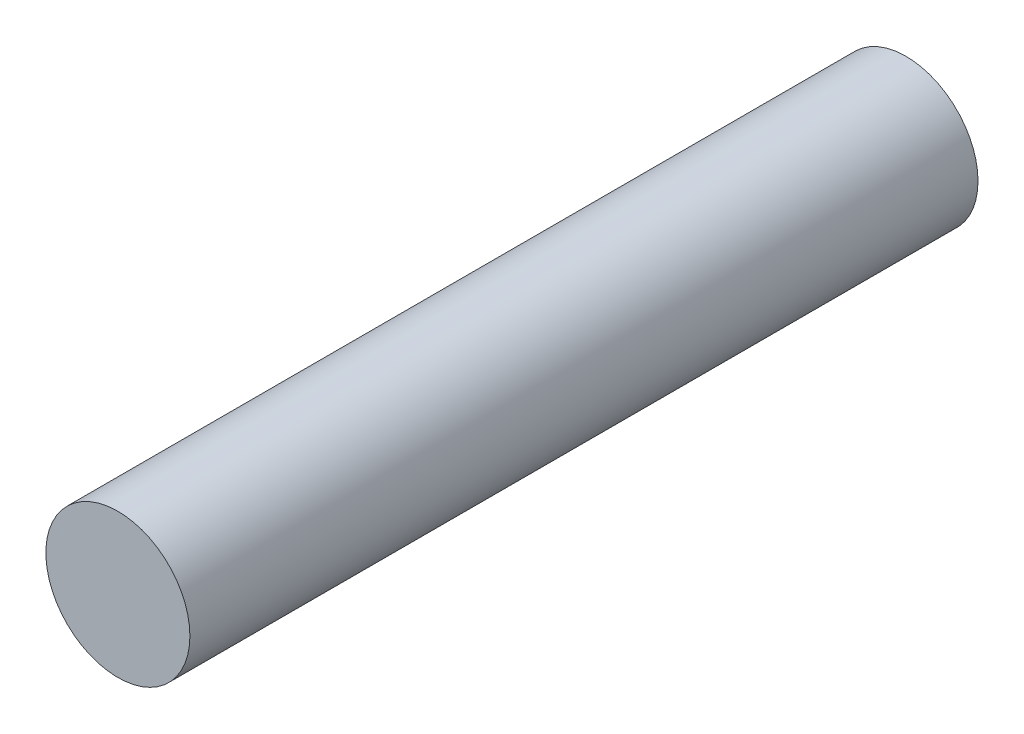
SolidWorks part; units mm, degrees
material "6061 Alloy"
ref_plane "Front Plane" through (0, 0, 0) normal (0, 0, 1) x (1, 0, 0)
ref_plane "Top Plane" through (0, 0, 0) normal (0, 1, 0) x (1, 0, 0)
ref_plane "Right Plane" through (0, 0, 0) normal (1, 0, 0) x (0, 0, -1)
sketch "Sketch1" plane through (0, 0, 0) normal (0, 0, 1) x (1, 0, 0)
  circle A0 centre (0, 0) radius 4.1783
  dimension "D1" = 8.3566
extrude "Boss-Extrude1" add sketch "Sketch1" along normal blind 45.72
